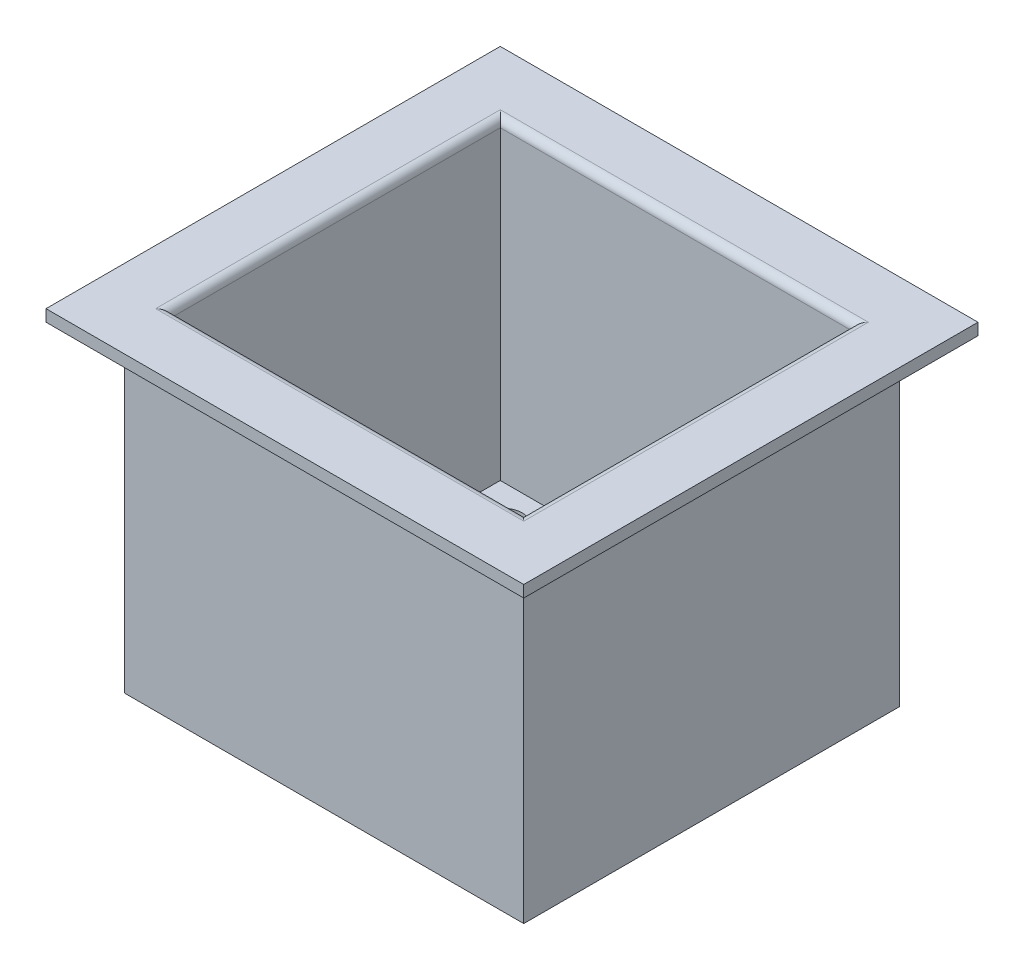
SolidWorks part; units mm, degrees
ref_plane "Front" through (0, 0, 0) normal (0, 0, 1) x (1, 0, 0)
ref_plane "Top" through (0, 0, 0) normal (0, 1, 0) x (1, 0, 0)
ref_plane "Right" through (0, 0, 0) normal (1, 0, 0) x (0, 0, -1)
sketch "Sketch1" plane through (0, 0, 0) normal (0, 1, 0) x (1, 0, 0)
  line L1 (-88.408, 41.8392) -> (13.592, 41.8392)
  line L2 (-88.408, 41.8392) -> (-88.408, -54.1608)
  line L3 (-88.408, -54.1608) -> (13.592, -54.1608)
  line L4 (13.592, 41.8392) -> (13.592, -54.1608)
extrude "Boss-Extrude1" add sketch "Sketch1" along normal blind 85
sketch "Sketch3" plane through (0, 85, 0) normal (0, 1, 0) x (1, 0, 0)
  line L4 (7.592, -48.1608) -> (4.592, -48.1608) construction
  line L5 (-82.408, -48.1608) -> (-79.408, -48.1608) construction
  line L8 (-82.408, 35.8392) -> (-82.408, -48.1608)
  line L9 (-82.408, -48.1608) -> (7.592, -48.1608)
  line L10 (7.592, -48.1608) -> (7.592, 35.8392)
  line L11 (7.592, 35.8392) -> (-82.408, 35.8392)
  line L12 (-82.408, 35.8392) -> (-82.408, -48.1608)
  line L13 (-82.408, -48.1608) -> (7.592, -48.1608)
  line L14 (7.592, -48.1608) -> (7.592, 35.8392)
  line L15 (7.592, 35.8392) -> (-82.408, 35.8392)
  dimension "D1" = 6
extrude "Cut-Extrude2" cut sketch "Sketch3" against normal blind 80
sketch "Sketch4" plane through (0, 85, 0) normal (0, 1, 0) x (1, 0, 0)
  line L5 (13.592, 41.8392) -> (-88.408, 41.8392)
  line L6 (13.592, 41.8392) -> (13.592, -54.1608)
  line L7 (13.592, -54.1608) -> (-88.408, -54.1608)
  line L8 (-98.408, 51.8392) -> (-98.408, -64.1608)
  line L9 (-98.408, -64.1608) -> (23.592, -64.1608)
  line L10 (23.592, -64.1608) -> (23.592, 51.8392)
  line L11 (23.592, 51.8392) -> (-98.408, 51.8392)
  line L12 (-98.408, 51.8392) -> (-98.408, -64.1608)
  line L13 (-98.408, -64.1608) -> (23.592, -64.1608)
  line L14 (23.592, -64.1608) -> (23.592, 51.8392)
  line L15 (23.592, 51.8392) -> (-98.408, 51.8392)
  line L16 (-88.408, 41.8392) -> (-88.408, -54.1608)
  dimension "D1" = 10
extrude "Boss-Extrude2" add sketch "Sketch4" against normal blind 3
sketch "Sketch5" plane through (0, 5, 0) normal (0, 1, 0) x (1, 0, 0)
  line L0 (7.592, 35.8392) -> (-82.408, -48.1608) construction
  line L1 (-82.408, 35.8392) -> (7.592, -48.1608) construction
  circle A0 centre (-37.408, -6.1608) radius 15
  circle A1 centre (-37.408, -6.1608) radius 10
extrude "Boss-Extrude3" add sketch "Sketch5" along normal blind 10
sketch "Sketch8" plane through (0, 5, 0) normal (0, 1, 0) x (1, 0, 0)
  circle A0 centre (-37.408, -6.1608) radius 10
extrude "Cut-Extrude3" cut sketch "Sketch8" against normal blind 10
sketch "Sketch9" plane through (7.592, 0, 0) normal (-1, 0, 0) x (0, 0, 1)
  line L0 (6.1608, 5) -> (6.1608, 15) construction
  line L1 (48.1608, 5) -> (-35.8392, 5) construction
  circle A0 centre (6.1608, 10) radius 1.5
extrude "Cut-Extrude4" cut sketch "Sketch9" along normal blind 80
sketch "Sketch10" plane through (0, 5, 0) normal (0, 1, 0) x (1, 0, 0)
  line L0 (-82.408, 35.8392) -> (-82.408, 25.8392) construction
  line L1 (-82.408, 35.8392) -> (-82.408, -48.1608) construction
  line L2 (7.592, -48.1608) -> (1.9028, -42.8508) construction
  line L3 (-82.408, 35.8392) -> (7.592, -48.1608) construction
  line L4 (7.592, -48.1608) -> (-2.408, -48.1608) construction
  line L5 (-82.408, -48.1608) -> (7.592, -48.1608) construction
  line L6 (-2.408, -48.1608) -> (-2.408, -38.8275) construction
  line L7 (-82.408, -48.1608) -> (-72.408, -48.1608) construction
  line L8 (-72.408, -48.1608) -> (-72.408, -38.8275) construction
  line L9 (-82.408, 35.8392) -> (-72.408, 35.8392) construction
  line L10 (7.592, 35.8392) -> (-82.408, 35.8392) construction
  line L11 (-72.408, 35.8392) -> (-72.408, 26.4874) construction
  line L12 (7.592, 35.8392) -> (-2.408, 35.8392) construction
  line L13 (-2.408, 35.8392) -> (-2.408, 26.4874) construction
  circle A0 centre (-2.408, 26.4874) radius 5
  circle A1 centre (-2.408, -38.8275) radius 5
  circle A2 centre (-72.408, -38.8275) radius 5
  circle A3 centre (-72.408, 26.4874) radius 5
extrude "切除-拉伸1" cut sketch "Sketch10" against normal blind 1
fillet "圆角2" radius 2 4 edges at (-37.408, 85, -35.8392) (-82.408, 85, 6.1608) (-37.408, 85, 48.1608) (7.592, 85, 6.1608)
